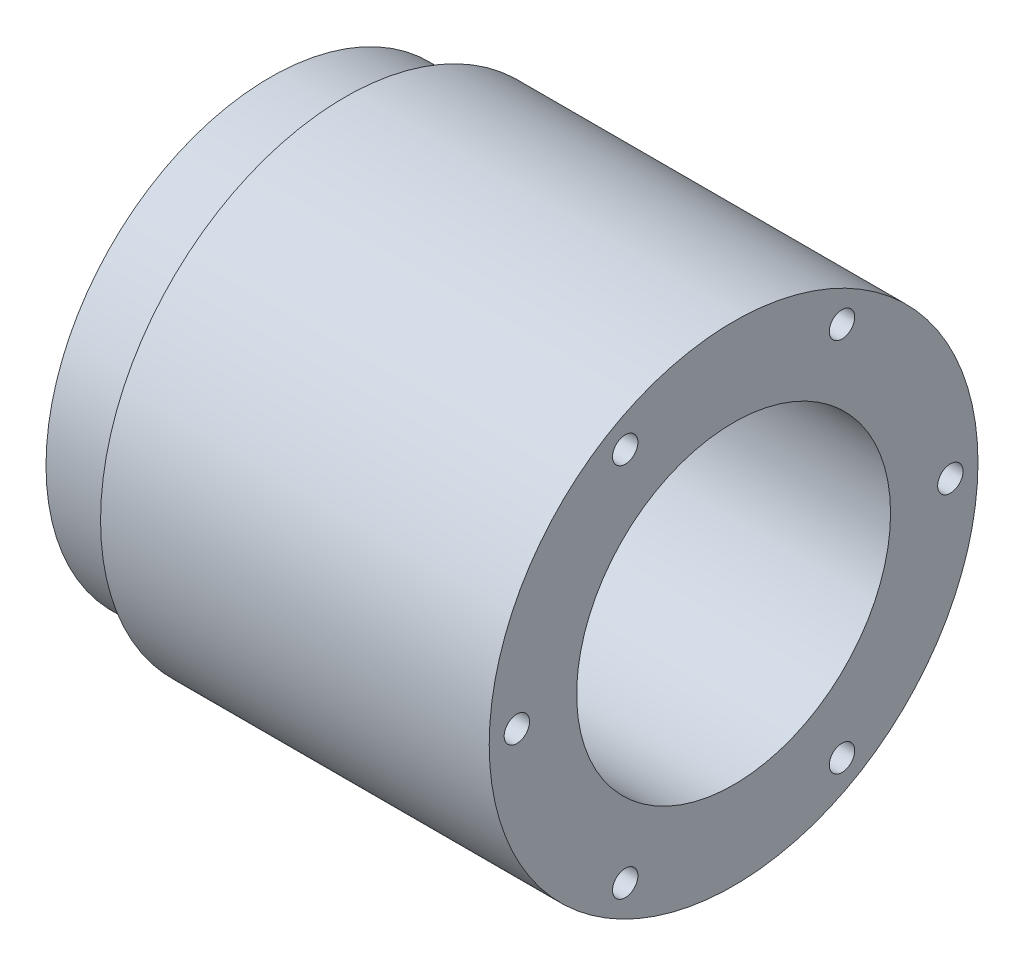
SolidWorks part; units mm, degrees
material "6063-T5"
ref_plane "Front" through (0, 0, 0) normal (0, 0, 1) x (1, 0, 0)
ref_plane "Top" through (0, 0, 0) normal (0, 1, 0) x (1, 0, 0)
ref_plane "Right" through (0, 0, 0) normal (1, 0, 0) x (0, 0, -1)
sketch "Croquis1" plane through (0, 0, 0) normal (1, 0, 0) x (0, 0, -1)
  circle A0 centre (0, 0) radius 21
  circle A1 centre (0, 0) radius 32.7
  dimension "D1" = 42
  dimension "D2" = 65.4
extrude "Saliente-Extruir1" add sketch "Croquis1" along normal mid plane 47
sketch "Croquis3" plane through (-23.5, 0, 0) normal (-1, 0, 0) x (0, 0, 1)
  line L5 (0, -34.925) -> (0, 34.925) construction
  line L6 (-18, 21) -> (18, 21)
  line L15 (-21, 18) -> (-21, -18)
  line L16 (-18, -21) -> (18, -21)
  line L17 (21, 18) -> (21, -18)
  line L18 (34.925, 0) -> (-34.925, 0) construction
  arc A2 (18, -21) -> (21, -18) centre (18, -18) ccw
  arc A3 (-21, -18) -> (-18, -21) centre (-18, -18) ccw
  arc A4 (-18, 21) -> (-21, 18) centre (-18, 18) ccw
  arc A5 (18, 21) -> (21, 18) centre (18, 18) cw
  circle A6 centre (0, 0) radius 32.7 construction
  circle A7 centre (0, 0) radius 32.7
  point P4 (0, 21)
  point P7 (21, 0)
  point P12 (21, -21)
  point P19 (21, 21)
  dimension "D2" = 3
  dimension "D1" = 42
extrude "Saliente-Extruir3" add sketch "Croquis3" along normal blind 5
sketch "Croquis4" plane through (-23.5, 0, 0) normal (-1, 0, 0) x (0, 0, 1)
  line L1 (-15.5, -15.5) -> (15.5, -15.5) construction
  line L2 (-15.5, -15.5) -> (-15.5, 15.5) construction
  line L3 (-15.5, 15.5) -> (15.5, 15.5) construction
  line L4 (15.5, -15.5) -> (15.5, 15.5) construction
  line L5 (-15.5, -15.5) -> (15.5, 15.5) construction
  line L6 (-15.5, 15.5) -> (15.5, -15.5) construction
  circle A0 centre (15.5, 15.5) radius 3.5
  circle A1 centre (-15.5, 15.5) radius 3.5
  circle A2 centre (-15.5, -15.5) radius 3.5
  circle A3 centre (15.5, -15.5) radius 3.5
  point P0 (0, 0)
  dimension "D2" = 7
  dimension "D1" = 31
extrude "Cortar-Extruir1" cut sketch "Croquis4" against normal blind 6
ref_plane "Plano1" through (0, -21, 0) normal (0, 1, 0) x (1, 0, 0)
ref_plane "Plano2" through (0, -45, 0) normal (0, 1, 0) x (1, 0, 0)
sketch "Croquis20" plane through (0, 0, 0) normal (0, 1, 0) x (1, 0, 0)
  line L0 (7.0135, 0) -> (-2.5, 0) construction
  line L1 (-28.6, 0) -> (28.6, 0) construction
  line L2 (-2.5, 0) -> (-2.5, -8.6641) construction
  line L4 (23.5, -32.7) -> (23.5, 32.7) construction
  dimension "D1" = 26
sketch "Croquis21" plane through (-28.5, 0, 0) normal (-1, 0, 0) x (0, 0, 1)
  line L8 (18, 21) -> (0, 21) construction
  line L9 (21, 0) -> (21, 18) construction
  line L10 (21, -18) -> (21, 0) construction
  line L11 (0, -21) -> (18, -21) construction
  line L12 (-18, -21) -> (0, -21) construction
  line L13 (-21, 0) -> (-21, -18) construction
  line L14 (-21, 18) -> (-21, 0) construction
  line L15 (0, 21) -> (-18, 21) construction
  line L16 (18, 21) -> (0, 21)
  line L17 (21, 0) -> (21, 18)
  line L18 (21, -18) -> (21, 0)
  line L19 (0, -21) -> (18, -21)
  line L20 (-18, -21) -> (0, -21)
  line L21 (-21, 0) -> (-21, -18)
  line L22 (-21, 18) -> (-21, 0)
  line L23 (0, 21) -> (-18, 21)
  circle A0 centre (0, 0) radius 30
  arc A9 (21, 18) -> (18, 21) centre (18, 18) ccw construction
  arc A10 (18, -21) -> (21, -18) centre (18, -18) ccw construction
  arc A11 (-21, -18) -> (-18, -21) centre (-18, -18) ccw construction
  arc A12 (-18, 21) -> (-21, 18) centre (-18, 18) ccw construction
  arc A13 (21, 18) -> (18, 21) centre (18, 18) ccw
  arc A14 (18, -21) -> (21, -18) centre (18, -18) ccw
  arc A15 (-21, -18) -> (-18, -21) centre (-18, -18) ccw
  arc A16 (-18, 21) -> (-21, 18) centre (-18, 18) ccw
  dimension "D1" = 60
extrude "Saliente-Extruir4" add sketch "Croquis21" along normal blind 10
hole_wizard "Taladro de margen para M31" positions "Croquis22" profile "Croquis24" hole size "M3" standard "Ansi Metric"
sketch "Croquis22" plane through (23.5, 0, 0) normal (1, 0, 0) x (0, 0, -1)
  line L2 (28.6, 0) -> (-28.6, 0) construction
  line L3 (0, 28.6) -> (0, -28.6) construction
  point P0 (29, 0)
  point P8 (14.5, -25.1147)
  point P9 (-14.5, -25.1147)
  point P10 (-29, 0)
  point P11 (-14.5, 25.1147)
  point P12 (14.5, 25.1147)
  dimension "D2" = 29
  dimension "D3" = 29
  dimension "D1" = 6
sketch "Croquis24" plane through (23.5, 0, -29) normal (0, 1, 0) x (0, 0, -1)
  line L0 (0, 0) -> (0, 11.0215)
  line L1 (0, 11.0215) -> (1.7, 10)
  line L2 (1.7, 10) -> (1.7, 0)
  line L5 (1.7, 0) -> (0, 0)
  line L10 (0, 11.0215) -> (-1.7, 10) construction
  line L11 (0, -6.35) -> (0, 107.95) construction
  dimension "Diámetro de taladro" = 3.4
  dimension "Profundidad de taladro" = 10
  dimension "Ángulo de perforador" = 118
